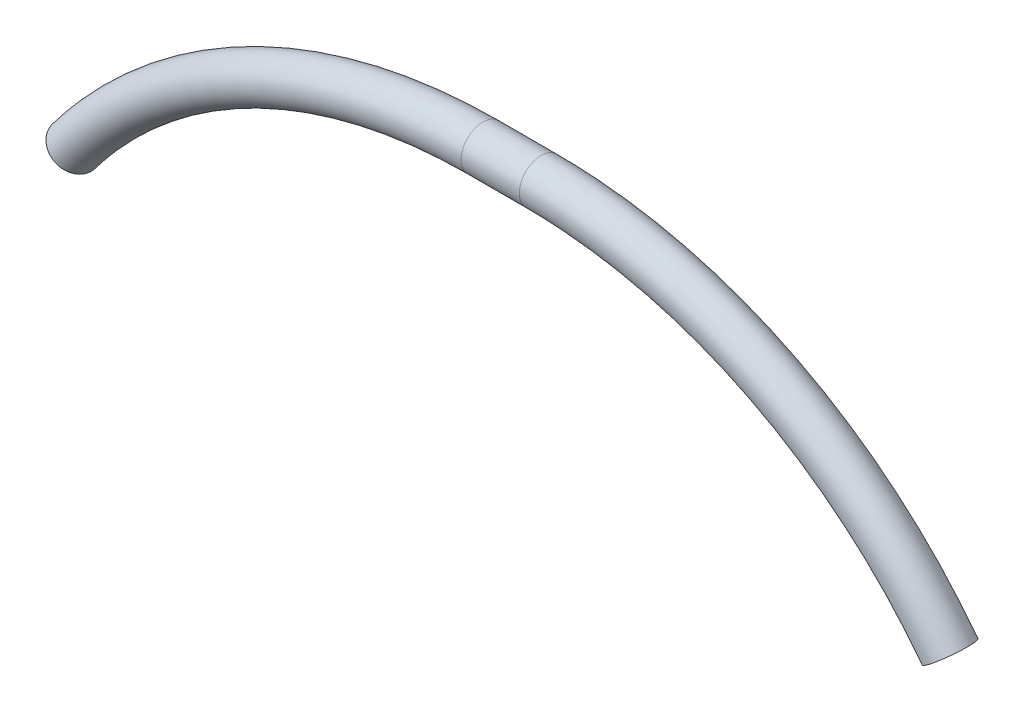
SolidWorks part; units mm, degrees
material "PPE"
ref_plane "Front" through (0, 0, 0) normal (0, 0, 1) x (1, 0, 0)
ref_plane "Top" through (0, 0, 0) normal (0, 1, 0) x (1, 0, 0)
ref_plane "Right" through (0, 0, 0) normal (1, 0, 0) x (0, 0, -1)
sketch "Sketch1" plane through (0, 0, 0) normal (1, 0, 0) x (0, 0, -1)
  circle A0 centre (0, 0) radius 4.7625
  circle A1 centre (0, 0) radius 3.175
  point P4 (4.7625, 0)
  point P5 (3.175, 0)
  dimension "OD" = 9.525
  dimension "ID" = 6.35
  dimension "Wall" = 1.5875
extrude "Extrude1" add sketch "Sketch1" along normal mid plane 12.7
sketch "Sketch2" plane through (0, 0, 0) normal (0, 0, 1) x (1, 0, 0)
  line L0 (-6.35, 0) -> (6.35, 0) construction
  line L1 (-6.35, 4.7625) -> (-6.35, -4.7625) construction
  line L2 (6.35, -4.7625) -> (6.35, 4.7625) construction
  line L3 (-95.6421, -44.45) -> (95.6421, -44.45) construction
  line L4 (0, 0) -> (0, -44.45) construction
  arc A0 (-6.35, 0) -> (-95.6421, -44.45) centre (-6.35, -111.911) ccw
  arc A1 (6.35, 0) -> (95.6421, -44.45) centre (6.35, -111.911) cw
  dimension "D1" = 44.45
  dimension "D2" = 191.2842
sketch "Sketch3" plane through (-6.35, 0, 0) normal (-1, 0, 0) x (0, 0, 1)
  circle A0 centre (0, 0) radius 3.175 construction
  circle A1 centre (0, 0) radius 3.175
  circle A2 centre (0, 0) radius 4.7625 construction
  circle A3 centre (0, 0) radius 4.7625
sketch "Sketch6" plane through (0, 0, 0) normal (0, 0, 1) x (1, 0, 0)
  arc A0 (-6.35, 0) -> (-95.6421, -44.45) centre (-6.35, -111.911) ccw construction
  arc A1 (-6.35, 0) -> (-95.6421, -44.45) centre (-6.35, -111.911) ccw
sketch "Sketch4" plane through (0, 0, 0) normal (0, 0, 1) x (1, 0, 0)
  arc A0 (95.6421, -44.45) -> (6.35, 0) centre (6.35, -111.911) ccw construction
  arc A1 (95.6421, -44.45) -> (6.35, 0) centre (6.35, -111.911) ccw
sketch "Sketch5" plane through (6.35, 0, 0) normal (1, 0, 0) x (0, 0, -1)
  circle A0 centre (0, 0) radius 3.175 construction
  circle A1 centre (0, 0) radius 3.175
  circle A2 centre (0, 0) radius 4.7625 construction
  circle A3 centre (0, 0) radius 4.7625
sweep "Sweep1" add profiles "Sketch3" path "Sketch6"
sweep "Sweep2" add profiles "Sketch5" path "Sketch4"
